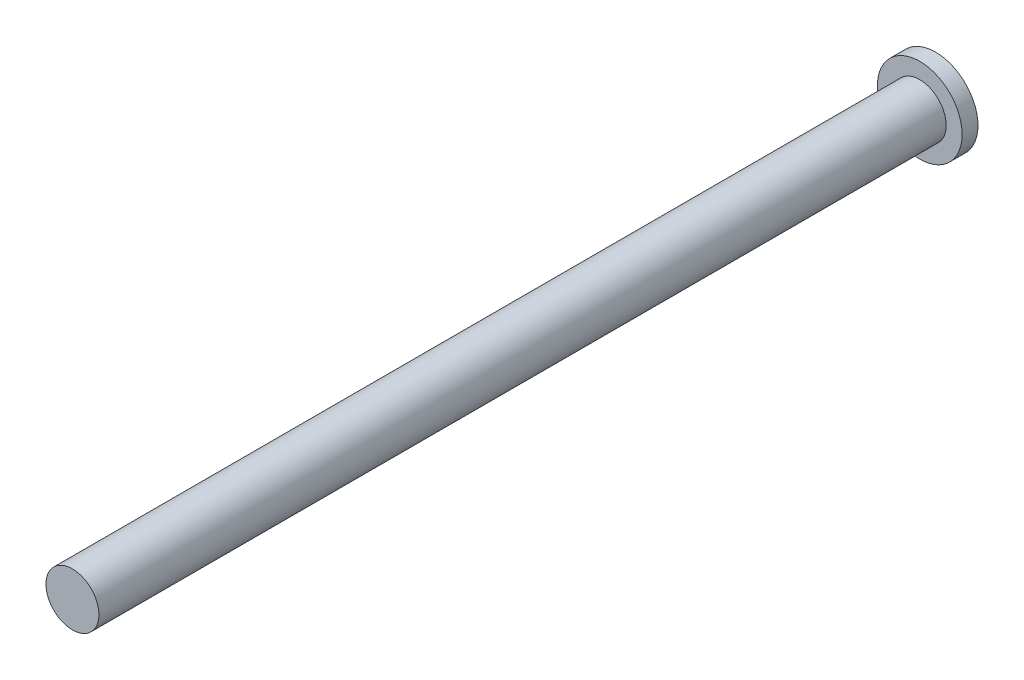
SolidWorks part; units mm, degrees
ref_plane "Front Plane" through (0, 0, 0) normal (0, 0, 1) x (1, 0, 0)
ref_plane "Top Plane" through (0, 0, 0) normal (0, 1, 0) x (1, 0, 0)
ref_plane "Right Plane" through (0, 0, 0) normal (1, 0, 0) x (0, 0, -1)
sketch "Sketch1" plane through (0, 0, 0) normal (0, 0, 1) x (1, 0, 0)
  circle A0 centre (0, 0) radius 4
extrude "Boss-Extrude1" add sketch "Sketch1" along normal blind 1.5
sketch "Sketch2" plane through (0, 0, 1.5) normal (0, 0, 1) x (1, 0, 0)
  circle A0 centre (0, 0) radius 2.5
extrude "Boss-Extrude2" add sketch "Sketch2" along normal blind 80
